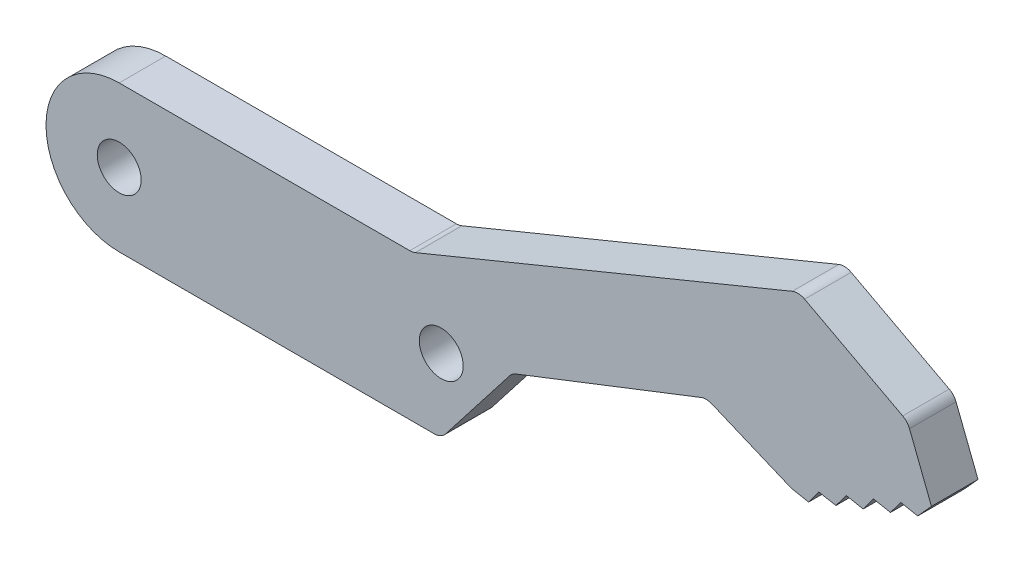
SolidWorks part; units mm, degrees
ref_plane "Front Plane" through (0, 0, 0) normal (0, 0, 1) x (1, 0, 0)
ref_plane "Top Plane" through (0, 0, 0) normal (0, 1, 0) x (1, 0, 0)
ref_plane "Right Plane" through (0, 0, 0) normal (1, 0, 0) x (0, 0, -1)
sketch "Sketch2" plane through (0, 0, 0) normal (0, 0, 1) x (1, 0, 0)
  line L0 (0, 0) -> (22, 0) construction
  line L1 (0, 5) -> (22, 5)
  line L2 (0, -5) -> (22, -5)
  line L3 (20.05, 5) -> (23.8167, -4.6583) construction
  line L4 (20.05, 5) -> (51.4959, 17.929) construction
  line L5 (23.8167, -4.6583) -> (55.4877, 7.6934) construction
  line L6 (51.4959, 17.929) -> (55.4877, 7.6934) construction
  line L9 (22, -5) -> (0, -5.0289)
  line L11 (20.05, 5) -> (46.409, 15.8375)
  line L12 (46.409, 15.8375) -> (53.8527, 11.8859)
  line L13 (53.8527, 11.8859) -> (55.4877, 7.6934)
  line L14 (55.4877, 7.6934) -> (45.9383, 3.9691)
  line L15 (45.9383, 3.9691) -> (40.1128, 6.4053)
  line L16 (40.1128, 6.4053) -> (26.846, 1.2312)
  line L17 (45.9383, 3.9691) -> (47.097, 3.7502)
  line L18 (47.097, 3.7502) -> (47.8016, 4.6958)
  line L19 (47.097, 3.7502) -> (54.5502, 6.6569) construction
  line L20 (47.8016, 4.6958) -> (48.9603, 4.4769)
  line L21 (48.9603, 4.4769) -> (49.6649, 5.4225)
  line L22 (49.6649, 5.4225) -> (50.8236, 5.2036)
  line L23 (50.8236, 5.2036) -> (51.5282, 6.1492)
  line L24 (51.5282, 6.1492) -> (52.6869, 5.9303)
  line L25 (52.6869, 5.9303) -> (53.3915, 6.8759)
  line L26 (53.3915, 6.8759) -> (54.5502, 6.6569)
  line L27 (54.5502, 6.6569) -> (55.4877, 7.6934)
  line L28 (26.846, 1.2312) -> (22, -5)
  arc A0 (0, 5) -> (0, -5) centre (0, 0) ccw
  arc A1 (22, -5) -> (22, 5) centre (22, 0) ccw
  circle A4 centre (22, 0) radius 1.5
  circle A5 centre (0, 0) radius 1.5
  point P3 (11, 0)
  dimension "D10" = 3
  dimension "D11" = 3
  dimension "D1" = 22
  dimension "D2" = 157.65
  dimension "D3" = 1.95
  dimension "D4" = 34
  dimension "D5" = 14.24
  dimension "D6" = 10.25
  dimension "D7" = 4.5
  dimension "D8" = 5.5
  dimension "D9" = 136
  dimension "D12" = 2
  dimension "D13" = 0.625
  dimension "D14" = 8
  dimension "D15" = 10
extrude "Boss-Extrude1" add sketch "Sketch2" along normal blind 3.18 contours L28 A1 L1 A0 L2 A5 A4 | A1 L16 L15 L14 L13 L12 L11 L1 | L17 L18 L14 | L20 L21 L14 | L22 L23 L14 | L24 L25 L14 | L26 L27 L14
fillet "Fillet1" radius 1 6 edges at (20.05, 5, 1.59) (46.409, 15.8375, 1.59) (53.8527, 11.8859, 1.59) (40.1128, 6.4053, 1.59) (26.846, 1.2312, 1.59) (22, -5, 1.59)
